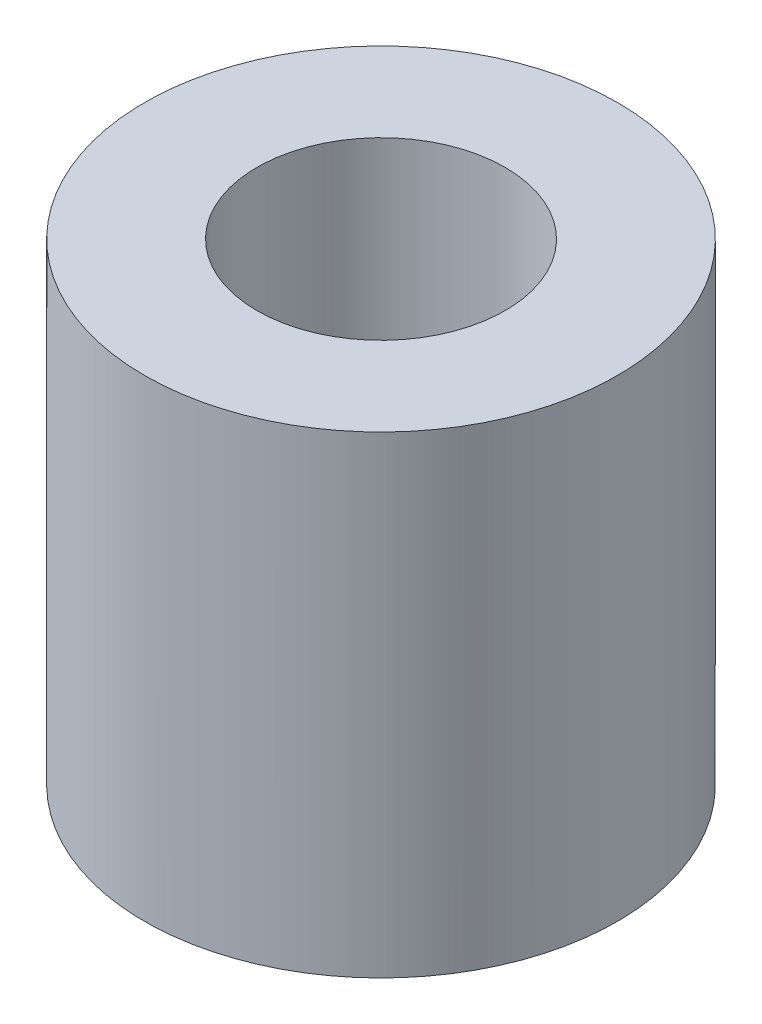
SolidWorks part; units mm, degrees
material "PE Low/Medium Density"
ref_plane "Front Plane" through (0, 0, 0) normal (0, 0, 1) x (1, 0, 0)
ref_plane "Top Plane" through (0, 0, 0) normal (0, 1, 0) x (1, 0, 0)
ref_plane "Right Plane" through (0, 0, 0) normal (1, 0, 0) x (0, 0, -1)
sketch "Sketch1" plane through (0, 0, 0) normal (0, 1, 0) x (1, 0, 0)
  circle A0 centre (0, 0) radius 4.0005
  circle A1 centre (0, 0) radius 7.62
  dimension "D1" = 8.001
  dimension "D2" = 15.24
extrude "Boss-Extrude1" add sketch "Sketch1" along normal blind 12.7
sketch "Sketch2" plane through (0, 0, 0) normal (0, -1, 0) x (1, 0, 0)
  circle A0 centre (0, 0) radius 7.62 construction
  circle A1 centre (0, 0) radius 7.62
extrude "Boss-Extrude2" add sketch "Sketch2" along normal blind 2.54
